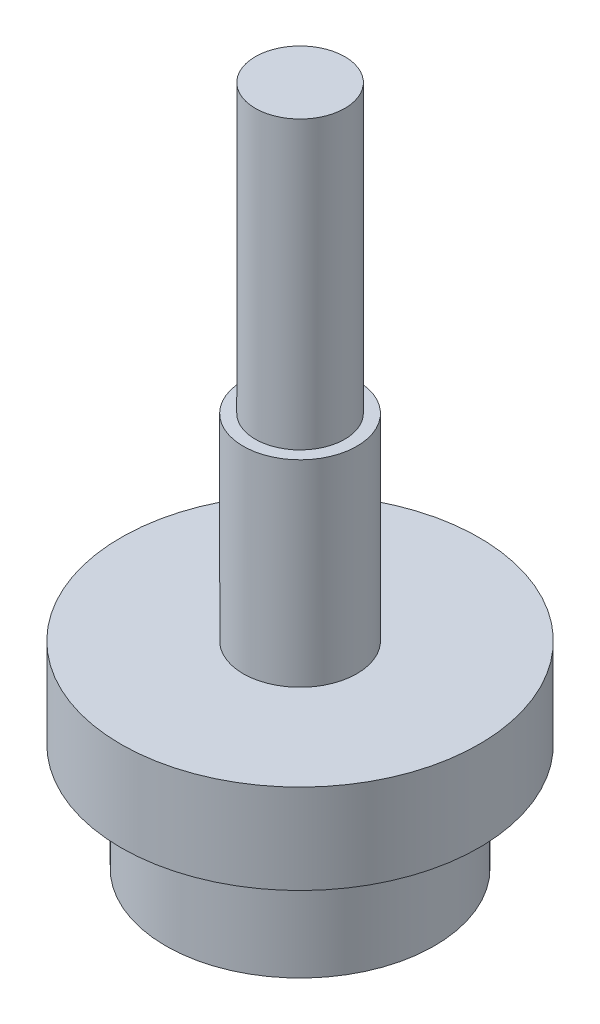
SolidWorks part; units mm, degrees
ref_plane "前视基准面" through (0, 0, 0) normal (0, 0, 1) x (1, 0, 0)
ref_plane "上视基准面" through (0, 0, 0) normal (0, 1, 0) x (1, 0, 0)
ref_plane "右视基准面" through (0, 0, 0) normal (1, 0, 0) x (0, 0, -1)
other "Configuration Table"
sketch "草图1" plane through (0, 0, 0) normal (0, 1, 0) x (1, 0, 0)
  circle A0 centre (0, 0) radius 2.5
  dimension "D1" = 5
extrude "凸台-拉伸1" add sketch "草图1" along normal blind 4
ref_plane "基准面1" through (0, 4, 0) normal (0, 1, 0) x (1, 0, 0)
ref_plane "基准面2" through (0, 4, 0) normal (0, 1, 0) x (1, 0, 0)
sketch "草图3" plane through (0, 4, 0) normal (0, 1, 0) x (1, 0, 0)
  circle A0 centre (0, 0) radius 7.5
  dimension "D1" = 15
extrude "凸台-拉伸3" add sketch "草图3" along normal blind 6
ref_plane "基准面3" through (0, 10, 0) normal (0, 1, 0) x (1, 0, 0)
sketch "草图4" plane through (0, 10, 0) normal (0, 1, 0) x (1, 0, 0)
  circle A0 centre (0, 0) radius 10
  dimension "D1" = 20
extrude "凸台-拉伸4" add sketch "草图4" along normal blind 5
ref_plane "基准面4" through (0, 15, 0) normal (0, 1, 0) x (1, 0, 0)
sketch "草图5" plane through (0, 15, 0) normal (0, 1, 0) x (1, 0, 0)
  circle A0 centre (0, 0) radius 3.175
  dimension "D1" = 6.35
extrude "凸台-拉伸5" add sketch "草图5" along normal blind 11
ref_plane "基准面5" through (0, 26, 0) normal (0, 1, 0) x (1, 0, 0)
sketch "草图6" plane through (0, 26, 0) normal (0, 1, 0) x (1, 0, 0)
  circle A0 centre (0, 0) radius 10
  dimension "D1" = 20
extrude "凸台-拉伸6" add sketch "草图6" along normal blind 5
ref_plane "基准面6" through (0, 31, 0) normal (0, 1, 0) x (1, 0, 0)
sketch "草图7" plane through (0, 31, 0) normal (0, 1, 0) x (1, 0, 0)
  circle A0 centre (0, 0) radius 7.5
  dimension "D1" = 15
extrude "凸台-拉伸7" add sketch "草图7" along normal blind 7
ref_plane "基准面7" through (0, 38, 0) normal (0, 1, 0) x (1, 0, 0)
sketch "草图8" plane through (0, 38, 0) normal (0, 1, 0) x (1, 0, 0)
  circle A0 centre (0, 0) radius 2.5
  dimension "D1" = 5
extrude "凸台-拉伸8" add sketch "草图8" along normal blind 4
sketch "草图9" plane through (0, 26, 0) normal (0, 1, 0) x (1, 0, 0)
  circle A0 centre (0, 0) radius 10
  dimension "D1" = 20
ref_plane "基准面8" through (0, 0, 0) normal (0, -1, 0) x (-1, 0, 0)
sketch "草图10" plane through (0, 0, 0) normal (0, -1, 0) x (-1, 0, 0)
  circle A0 centre (0, 0) radius 2.5
extrude "切除-拉伸1" cut sketch "草图10" against normal blind 1 and the other way through all
sketch "草图11" plane through (0, 15, 0) normal (0, 1, 0) x (1, 0, 0)
  circle A0 centre (0, 0) radius 2.5
  circle A1 centre (0, 0) radius 10
sketch "草图13" plane through (0, 26, 0) normal (0, -1, 0) x (1, 0, 0)
  circle A0 centre (0, 0) radius 2.5
  circle A1 centre (0, 0) radius 10
extrude "切除-拉伸3" cut sketch "草图13" against normal blind 15
sketch "草图14" plane through (0, 42, 0) normal (0, 1, 0) x (1, 0, 0)
  circle A0 centre (0, 0) radius 2.5
